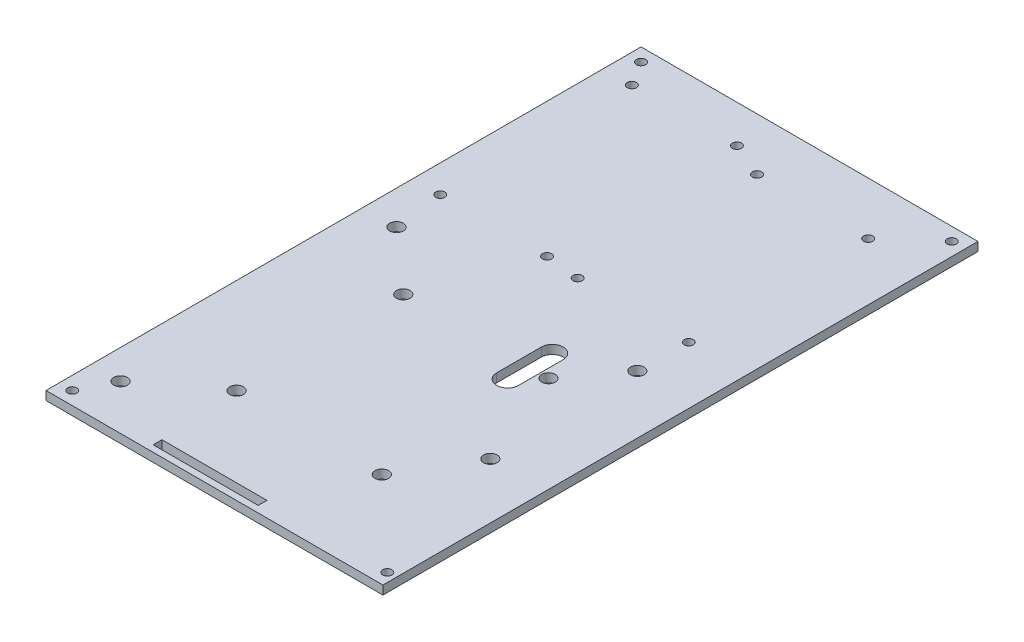
SolidWorks part; units mm, degrees
ref_plane "前视基准面" through (0, 0, 0) normal (0, 0, 1) x (1, 0, 0)
ref_plane "上视基准面" through (0, 0, 0) normal (0, 1, 0) x (1, 0, 0)
ref_plane "右视基准面" through (0, 0, 0) normal (1, 0, 0) x (0, 0, -1)
sketch "草图1" plane through (0, 0, 0) normal (0, 1, 0) x (1, 0, 0)
  line L0 (3.5, 127.4) -> (33.5, 127.4) construction
  line L1 (0, 0) -> (77, 0)
  line L2 (0, 0) -> (0, 136)
  line L3 (0, 136) -> (77, 136)
  line L4 (77, 0) -> (77, 136)
  line L5 (3.5, 76) -> (73.5, 76) construction
  line L6 (3.5, 76) -> (3.5, 6) construction
  line L7 (3.5, 6) -> (73.5, 6) construction
  line L8 (73.5, 76) -> (73.5, 6) construction
  line L13 (21.81, 59.84) -> (55.01, 59.84) construction
  line L14 (21.81, 59.84) -> (21.81, 21.74) construction
  line L15 (21.81, 21.74) -> (55.01, 21.74) construction
  line L16 (55.01, 59.84) -> (55.01, 21.74) construction
  line L17 (3.5, 130) -> (33.5, 130) construction
  line L18 (3.5, 130) -> (3.5, 81) construction
  line L19 (3.5, 81) -> (33.5, 81) construction
  line L20 (33.5, 130) -> (33.5, 81) construction
  line L21 (3.5, 83.8) -> (33.5, 83.8) construction
  line L22 (36.5, 124) -> (65.9, 124) construction
  line L23 (65.9, 126) -> (36.5, 126) construction
  line L24 (65.9, 126) -> (65.9, 81) construction
  line L25 (65.9, 81) -> (36.5, 81) construction
  line L26 (36.5, 126) -> (36.5, 81) construction
  line L27 (36.5, 83) -> (65.9, 83) construction
  line L28 (38.5, 126) -> (38.5, 81) construction
  line L29 (63.9, 126) -> (63.9, 81) construction
  line L30 (0, 3) -> (77, 3) construction
  line L31 (3, 136) -> (3, 0) construction
  line L32 (74, 136) -> (74, 0) construction
  line L33 (0, 133) -> (77, 133) construction
  line L34 (50.5, 65.2) -> (50.5, 55) construction
  line L35 (53, 65.2) -> (53, 55)
  line L36 (48, 65.2) -> (48, 55)
  line L38 (23, 1.5) -> (47, 1.5)
  line L39 (23, 1.5) -> (23, 3.5)
  line L40 (23, 3.5) -> (47, 3.5)
  line L41 (47, 1.5) -> (47, 3.5)
  circle A0 centre (7.71, 72.38) radius 1.55
  circle A1 centre (6.71, 10.34) radius 1.55
  circle A2 centre (63.71, 71.44) radius 1.55
  circle A3 centre (64.31, 37.24) radius 1.55
  circle A4 centre (21.81, 21.74) radius 1.55
  circle A5 centre (55.01, 21.74) radius 1.55
  circle A6 centre (21.81, 59.84) radius 1.55
  circle A7 centre (55.01, 59.84) radius 1.55
  circle A8 centre (6.5, 127.4) radius 1.05
  circle A9 centre (30.5, 127.4) radius 1.05
  circle A10 centre (6.3, 83.8) radius 1.05
  circle A11 centre (30.7, 83.8) radius 1.05
  circle A12 centre (38.5, 124) radius 1.05
  circle A13 centre (63.9, 124) radius 1.05
  circle A14 centre (38.5, 83) radius 1.05
  circle A15 centre (63.9, 83) radius 1.05
  circle A16 centre (3, 3) radius 1.05
  circle A17 centre (75, 3) radius 1.05
  circle A18 centre (3, 133) radius 1.05
  circle A19 centre (74, 133) radius 1.05
  arc A20 (53, 65.2) -> (48, 65.2) centre (50.5, 65.2) ccw
  arc A21 (48, 55) -> (53, 55) centre (50.5, 55) ccw
  point P77 (50.5, 60.1)
  dimension "D5" = 3.1
  dimension "D18" = 3.1
  dimension "D19" = 3.1
  dimension "D20" = 3.1
  dimension "D21" = 3.1
  dimension "D22" = 3.1
  dimension "D23" = 3.1
  dimension "D24" = 3.1
  dimension "D30" = 2.1
  dimension "D31" = 2.1
  dimension "D37" = 2.1
  dimension "D38" = 2.1
  dimension "D48" = 2.1
  dimension "D49" = 2.1
  dimension "D50" = 2.1
  dimension "D51" = 2.1
  dimension "D56" = 2.1
  dimension "D57" = 2.1
  dimension "D58" = 2.1
  dimension "D59" = 2.1
  dimension "D1" = 77
  dimension "D2" = 136
  dimension "D3" = 70
  dimension "D4" = 70
  dimension "D6" = 15.74
  dimension "D7" = 18.31
  dimension "D8" = 15.1
  dimension "D9" = 11.4
  dimension "D10" = 33.2
  dimension "D11" = 38.1
  dimension "D12" = 42.5
  dimension "D13" = 15.5
  dimension "D14" = 50.64
  dimension "D15" = 14.1
  dimension "D16" = 41.9
  dimension "D17" = 49.7
  dimension "D25" = 6
  dimension "D26" = 3.5
  dimension "D27" = 49
  dimension "D28" = 30
  dimension "D29" = 2.6
  dimension "D32" = 3
  dimension "D33" = 3
  dimension "D34" = 2.8
  dimension "D35" = 2.8
  dimension "D36" = 2.8
  dimension "D39" = 5
  dimension "D40" = 5
  dimension "D41" = 29.4
  dimension "D42" = 45
  dimension "D43" = 3
  dimension "D44" = 2
  dimension "D45" = 2
  dimension "D46" = 2
  dimension "D47" = 2
  dimension "D52" = 3
  dimension "D53" = 3
  dimension "D54" = 3
  dimension "D55" = 3
  dimension "D60" = 10.2
  dimension "D61" = 5
  dimension "D62" = 55
  dimension "D63" = 26.5
  dimension "D64" = 2
  dimension "D65" = 24
  dimension "D66" = 1.5
  dimension "D67" = 2
  dimension "D68" = 23
extrude "凸台-拉伸1" add sketch "草图1" along normal blind 2
